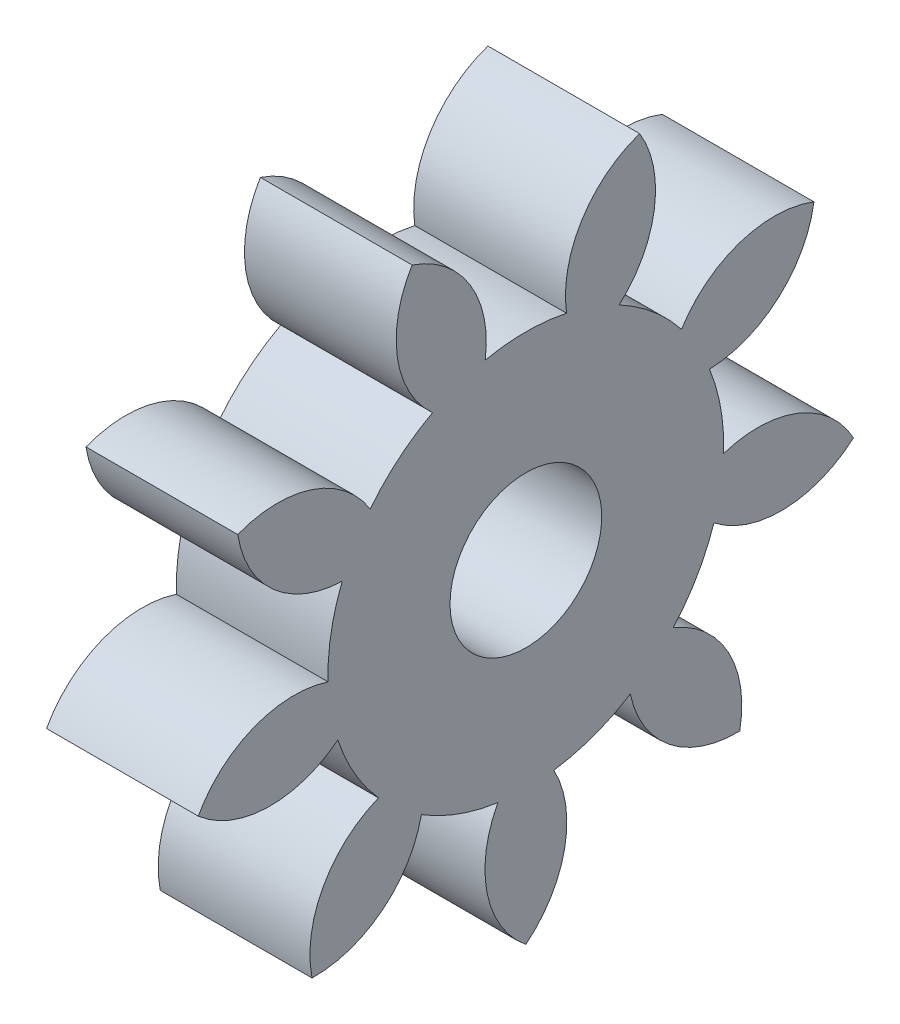
SolidWorks part; units mm, degrees
ref_plane "Plane1" through (0, 0, 0) normal (0, 0, 1) x (1, 0, 0)
ref_plane "Plane2" through (0, 0, 0) normal (0, 1, 0) x (1, 0, 0)
ref_plane "Plane3" through (0, 0, 0) normal (1, 0, 0) x (0, 0, -1)
sketch "HoldingSke" plane through (0, 0, 0) normal (0, 1, 0) x (1, 0, 0)
  line L0 (0, 0) -> (500.2823, -88.2133)
  line L1 (-15, 0) -> (100, 0) construction
  line L2 (0, 0) -> (-2.1039, 2.3779)
  line L3 (0, 0) -> (-11.863, 4.5341)
  line L4 (0, 0) -> (8.5048, 1.4996)
  line L5 (0, 0) -> (-47.5972, -17.7524)
  line L6 (0, 0) -> (-2.632, -1.7758)
  line L7 (-2.1039, 2.3779) -> (8.8308, 51.9871)
  line L8 (-76.2, 54.61) -> (-72.771, 54.61)
  line L9 (-71.009, 38.7566) -> (-53.1078, 45.2721)
  line L10 (-76.2, 71.12) -> (104.1128, 71.12)
  line L11 (0, 0) -> (-3.175, 0)
  line L12 (-76.2, 101.6) -> (-76.1492, 101.6)
  line L13 (24.9733, 27.94) -> (52.9518, 28.4284)
  line L14 (24.9733, 27.94) -> (25.0241, 27.9398)
  line L15 (24.9733, 27.94) -> (100.4021, 29.52)
  circle A0 centre (0, 0) radius 1.5875
  circle A1 centre (0, 0) radius 4.1402
  circle A2 centre (0, 0) radius 38.1
  circle A3 centre (0, 0) radius 1.5875
  dimension "MHD" = 8.2804
  dimension "Hub_dia" = 76.2
  dimension "Bore" = 3.175
  dimension "MBD" = 3.175
  dimension "Num_teeth" = 10
  dimension "Pitch_radius" = 180.3128
  dimension "Pitch" = 508
  dimension "Width" = 3.175
  dimension "Overall_len" = 50.8
  dimension "Show_teeth" = 10
  dimension "Thickness" = 3.175
  dimension "OAL" = 50.8001
  dimension "T_dim" = 3.429
  dimension "Ap" = 20
  dimension "H" = 19.05
  dimension "Backlash" = 0.0508
  dimension "Addendum_fac" = 1
  dimension "Dedendum_fac" = 1.2
  dimension "Clearance_fac" = 0.2
  dimension "Dedendum_add" = 0.0508
sketch "BasProSke" plane through (0, 0, 0) normal (0, 1, 0) x (1, 0, 0)
  line L0 (-10, 0) -> (60, 0) construction
  line L1 (0, 0) -> (0, 6.985)
  line L2 (0, 0) -> (3.175, 0)
  line L3 (3.175, 0) -> (3.175, 6.985)
  line L4 (3.175, 6.985) -> (0, 6.985)
  dimension "Diameter" = 13.97
  dimension "Thickness" = 3.175
revolve "Base-Revolve" add sketch "BasProSke" angle 360 about L0
sketch "TooCutSke" plane through (0, 0, 0) normal (1, 0, 0) x (0, 0, -1)
  line L1 (0, 0) -> (0, 107) construction
  line L2 (0, 0) -> (-1.1786, 5.5922) construction
  line L3 (0, 0) -> (-3.8703, 10.6336) construction
  line L4 (-1.1786, 5.5922) -> (-1.9352, 5.3168) construction
  arc A0 (0.8509, 4.0518) -> (-0.8509, 4.0518) centre (0, 0) ccw
  arc A1 (2.4581, 6.5653) -> (-2.4581, 6.5653) centre (0, 0) ccw
  circle A2 centre (0, 0) radius 5.715 construction
  circle A3 centre (0, 0) radius 5.3703 construction
  arc A4 (-0.8509, 4.0518) -> (-2.4581, 6.5653) centre (-3.1139, 4.3754) ccw
  arc A5 (2.4581, 6.5653) -> (0.8509, 4.0518) centre (3.1139, 4.3754) ccw
  dimension "Root_dia" = 8.2804
  dimension "Overcut_dia" = 14.0208
  dimension "Pitch_dia" = 11.43
  dimension "Base_dia" = 10.7407
  dimension "Flank_rad" = 2.286
  dimension "Half_ang" = 20
  dimension "Half_CT" = 0.8051
extrude "ToothCut" cut sketch "TooCutSke" along normal through all
fillet "Breaks" [suppressed] radius 0.0254
fillet "RootFillets" [suppressed] radius 0.3048
pattern_circular "TeethCuts" count 10 every 40 about axis through (-10, 0, 0) along (1, 0, 0) of "ToothCut"
sketch "HubNeaOneSke" plane through (0, 0, 0) normal (-1, 0, 0) x (0, 0, 1)
  circle A0 centre (0, 0) radius 4.1402
  dimension "Diameter" = 8.2804
extrude "HubNearOne" [suppressed] add sketch "HubNeaOneSke" along normal blind 47.6251
sketch "HubNeaBotSke" plane through (0, 0, 0) normal (-1, 0, 0) x (0, 0, 1)
  circle A0 centre (0, 0) radius 4.1402
  dimension "Diameter" = 8.2804
extrude "HubNearBoth" [suppressed] add sketch "HubNeaBotSke" along normal blind 23.8125
ref_plane "FarPln" through (3.175, 0, 0) normal (1, 0, 0) x (0, 0, -1)
sketch "HubFarSke" plane through (3.175, 0, 0) normal (1, 0, 0) x (0, 0, -1)
  circle A0 centre (0, 0) radius 4.1402
  dimension "Diameter" = 8.2804
extrude "HubFar" [suppressed] add sketch "HubFarSke" along normal blind 23.8125
sketch "BorSke" plane through (0, 0, 0) normal (1, 0, 0) x (0, 0, -1)
  circle A0 centre (0, 0) radius 1.5875
  dimension "Diameter" = 3.175
extrude "Bore" cut sketch "BorSke" along normal mid plane 101.6001
sketch "KeySke" plane through (0, 0, 0) normal (1, 0, 0) x (0, 0, -1)
  line L0 (-0.127, 0) -> (-0.127, 1.8415)
  line L1 (-0.127, 1.8415) -> (0.127, 1.8415)
  line L2 (0.127, 1.8415) -> (0.127, 0)
  line L3 (0, 0) -> (0, 34) construction
  line L4 (-0.127, 0) -> (0.127, 0)
  dimension "Offset" = 1.8415
  dimension "Width" = 0.254
extrude "Keyway" [suppressed] cut sketch "KeySke" along normal mid plane 101.6001
pattern_circular "Keyway2" [suppressed] count 2 every 90 about axis through (-10, 0, 0) along (1, 0, 0)
equation "' \"Pitch@HoldingSke\" = 4"
equation "' \"Num_teeth@HoldingSke\" = 12"
equation "' \"Ap@HoldingSke\" =  20"
equation "' \"Width@HoldingSke\" = 0.5"
equation "' \"Hub_dia@HoldingSke\"= 1"
equation "' \"Overall_len@HoldingSke\" = 1.0"
equation "' \"Bore@HoldingSke\" = 0.75"
equation "' \"T_dim@HoldingSke\" = 0.85"
equation "' \"Width@KeySke\" = 0.25"
equation "' \"Show_teeth@HoldingSke\" = 13"
equation "' \"Backlash@HoldingSke\" = 0.009"
equation "' \"Addendum_fac@HoldingSke\" = 1.0"
equation "' \"Dedendum_fac@HoldingSke\" = 1.25"
equation "' \"Dedendum_add@HoldingSke\" = 0.00005"
equation "' \"Clearance_fac@HoldingSke\" = 0.25"
equation "' \"Pitch@HoldingSke\" = 0.5"
equation "' \"Num_teeth@HoldingSke\" = 23"
equation "' \"Show_teeth@HoldingSke\" = 23"
equation "' \"Backlash@HoldingSke\" = 0.0375"
equation "\"Overcut_dia@TooCutSke\"=(9 + 2 * \"Addendum_fac@HoldingSke\") / \"Pitch@HoldingSke\" + 0.002"
equation "\"Pitch_dia@TooCutSke\"=9/ \"Pitch@HoldingSke\""
equation "\"Base_dia@TooCutSke\"=9 / \"Pitch@HoldingSke\" * cos((\"Ap@HoldingSke\"  * 3.14159265 / 180))"
equation "\"Root_dia@TooCutSke\"=(9 + 2) / \"Pitch@HoldingSke\" - 2 * (\"Addendum_fac@HoldingSke\" + \"Dedendum_fac@HoldingSke\") / \"Pitch@HoldingSke\" - \"Dedendum_add@HoldingSke\" * 2"
equation "\"Half_ang@TooCutSke\"=180 / 9"
equation "\"Half_CT@TooCutSke\"=9 / \"Pitch@HoldingSke\" * sin((3.14159265 / 2 / \"Num_teeth@HoldingSke\")) / 2 - 7 * \"Backlash@HoldingSke\" / 4"
equation "\"Flank_rad@TooCutSke\"=9/ \"Pitch@HoldingSke\" / 5"
equation "\"Radius@RootFillets\" = \"Clearance_fac@HoldingSke\" / \"Pitch@HoldingSke\" + \"Dedendum_add@HoldingSke\""
equation "\"Break_rad@Breaks\" = 0.02 / \"Pitch@HoldingSke\""
equation "\"Thickness@HoldingSke\" = \"Width@HoldingSke\""
equation "\"OAL@HoldingSke\" = \"Thickness@HoldingSke\""
equation "\"MHD@HoldingSke\" = (\"Num_teeth@HoldingSke\" + 2) / \"Pitch@HoldingSke\" - 2 * (\"Addendum_fac@HoldingSke\" + \"Dedendum_fac@HoldingSke\")  / \"Pitch@HoldingSke\" - \"Dedendum_add@HoldingSke\" * 2"
equation "\"MBD@HoldingSke\" = (\"Num_teeth@HoldingSke\" + 2) / \"Pitch@HoldingSke\" - 2 * (\"Addendum_fac@HoldingSke\" + \"Dedendum_fac@HoldingSke\")  / \"Pitch@HoldingSke\" - \"Dedendum_add@HoldingSke\" * 2 - 0.002"
equation "\"MHD@HoldingSke\" = ((sgn( \"MHD@HoldingSke\" - \"Hub_dia@HoldingSke\" )-1)*( \"MHD@HoldingSke\" - \"Hub_dia@HoldingSke\" ))/-2+ \"Hub_dia@HoldingSke\""
equation "\"MBD@HoldingSke\" = ((sgn( \"MBD@HoldingSke\" - \"Bore@HoldingSke\" )-1)*( \"MBD@HoldingSke\" - \"Bore@HoldingSke\" ))/-2+ \"Bore@HoldingSke\""
equation "\"OAL@HoldingSke\" = ((sgn( \"OAL@HoldingSke\" - \"Overall_len@HoldingSke\" )+1)*( \"OAL@HoldingSke\" - \"Overall_len@HoldingSke\" ))/2 + \"Overall_len@HoldingSke\" + 0.000002"
equation "\"Num_teeth@TeethCuts\"=int( 9 ) + 1"
equation "\"Num_teeth@TeethCuts\" = ((sgn( \"Num_teeth@TeethCuts\" - \"Num_teeth@HoldingSke\" )-1)*( \"Num_teeth@TeethCuts\" - \"Num_teeth@HoldingSke\" ))/-2+ \"Num_teeth@HoldingSke\""
equation "\"Num_teeth@TeethCuts\" = ((sgn( \"Num_teeth@TeethCuts\" - 2.0)+1)*( \"Num_teeth@TeethCuts\" - 2.0))/2 +2.0"
equation "\"Angle@TeethCuts\"=360.0 / 9"
equation "\"Diameter@BasProSke\"=(9 + 2 * \"Addendum_fac@HoldingSke\") / \"Pitch@HoldingSke\""
equation "\"Thickness@BasProSke\"=.125"
equation "' \"Fillet_rad@BasProSke\" =  \"Thickness@HoldingSke\" * 0.05"
equation "\"MHD@HoldingSke\" = ((sgn( \"MHD@HoldingSke\" - \"Root_dia@TooCutSke\" )-1)*( \"MHD@HoldingSke\" - \"Root_dia@TooCutSke\" ))/-2+ \"Root_dia@TooCutSke\""
equation "\"Diameter@HubNeaOneSke\" = \"MHD@HoldingSke\""
equation "\"Length@HubNearOne\" = \"OAL@HoldingSke\" - \"Thickness@BasProSke\""
equation "\"Diameter@HubNeaBotSke\" = \"MHD@HoldingSke\""
equation "\"Length@HubNearBoth\" = ( \"OAL@HoldingSke\" - \"Thickness@BasProSke\" ) / 2.0"
equation "\"Thickness@FarPln\" = \"Thickness@BasProSke\""
equation "\"Diameter@HubFarSke\" = \"MHD@HoldingSke\""
equation "\"Length@HubFar\" = ( \"OAL@HoldingSke\" - \"Thickness@BasProSke\" ) / 2.0"
equation "\"Diameter@BorSke\" = \"MBD@HoldingSke\""
equation "\"D1@Bore\" = \"OAL@HoldingSke\" * 2.0"
equation "\"D1@Keyway\" = \"OAL@HoldingSke\" * 2.0"
equation "\"Offset@KeySke\" = \"T_dim@HoldingSke\" - \"MBD@HoldingSke\" / 2.0"
